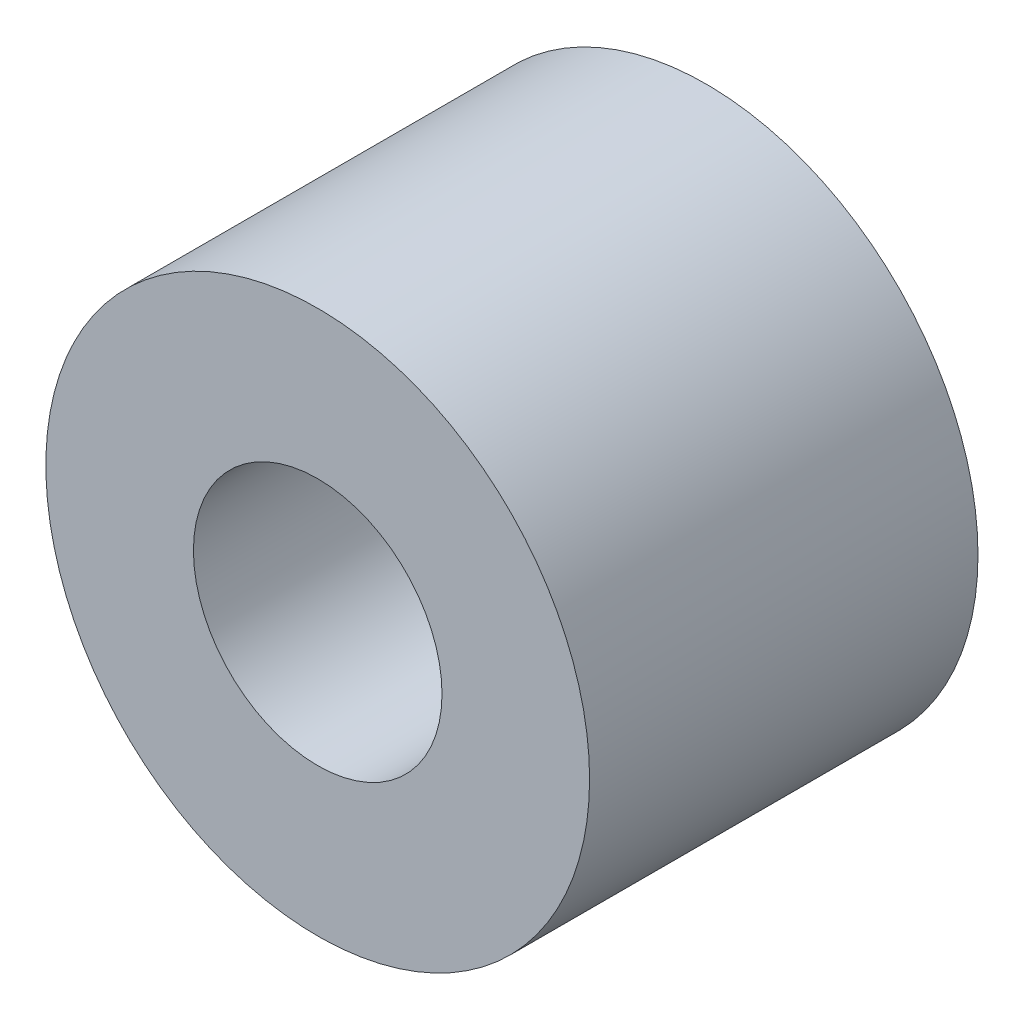
SolidWorks part; units mm, degrees
ref_plane "正面" through (0, 0, 0) normal (0, 0, 1) x (1, 0, 0)
ref_plane "平面" through (0, 0, 0) normal (0, 1, 0) x (1, 0, 0)
ref_plane "右側面" through (0, 0, 0) normal (1, 0, 0) x (0, 0, -1)
sketch "ｽｹｯﾁ1" plane through (0, 0, 0) normal (0, 0, 1) x (1, 0, 0)
  circle A0 centre (0, 0) radius 3.5
  circle A1 centre (0, 0) radius 1.6
  dimension "D1" = 7
  dimension "D2" = 3.2
extrude "ﾎﾞｽ - 押し出し1" add sketch "ｽｹｯﾁ1" along normal blind 5
